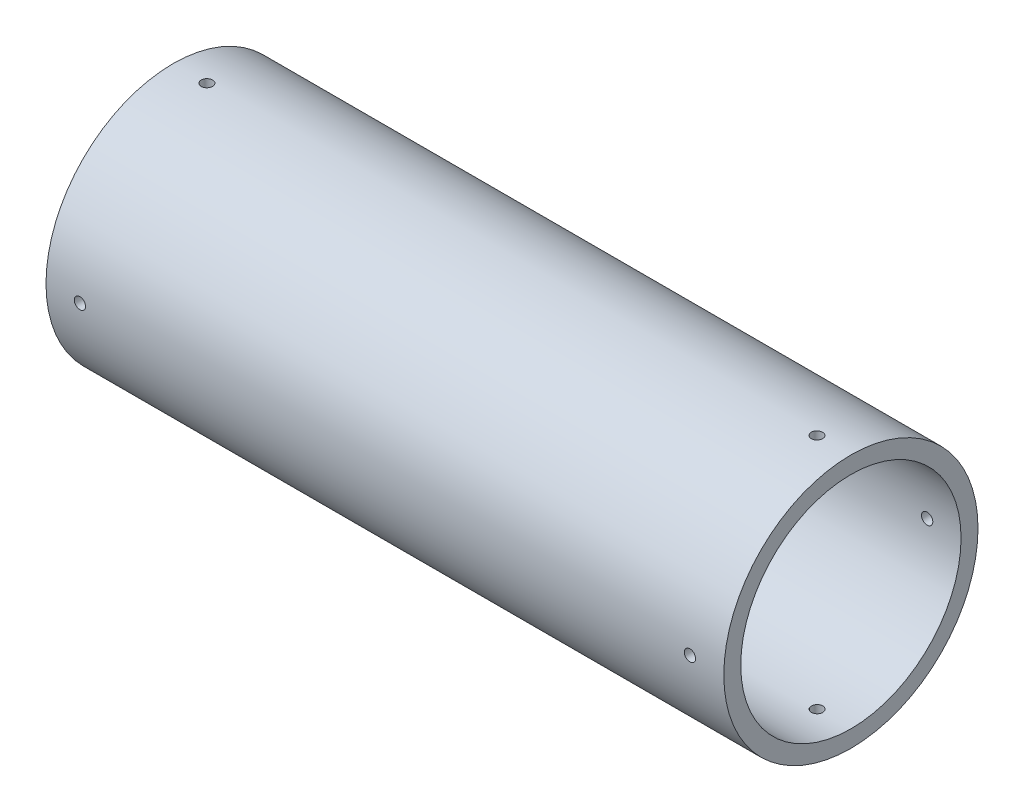
SolidWorks part; units mm, degrees
material "ABS"
ref_plane "Спереди" through (0, 0, 0) normal (0, 0, 1) x (1, 0, 0)
ref_plane "Сверху" through (0, 0, 0) normal (0, 1, 0) x (1, 0, 0)
ref_plane "Справа" through (0, 0, 0) normal (1, 0, 0) x (0, 0, -1)
sketch "Эскиз1" plane through (0, 0, 0) normal (1, 0, 0) x (0, 0, -1)
  circle A0 centre (0, 0) radius 22.5
  circle A1 centre (0, 0) radius 19.5
  dimension "D1" = 45
  dimension "D2" = 39
extrude "Бобышка-Вытянуть1" add sketch "Эскиз1" along normal blind 120
sketch "Эскиз2" plane through (120, 0, 0) normal (1, 0, 0) x (0, 0, -1)
  line L0 (0, 22.5) -> (0, -22.5) construction
  circle A0 centre (0, 0) radius 22.5 construction
ref_plane "Плоскость1" through (0, 22.5, 0) normal (0, 1, 0) x (1, 0, 0)
sketch "Эскиз3" plane through (0, 22.5, 0) normal (0, 1, 0) x (1, 0, 0)
  line L0 (60, 22.5) -> (60, -22.5) construction
  line L1 (120, 22.5) -> (0, 22.5) construction
  line L2 (0, -22.5) -> (120, -22.5) construction
  line L3 (0, 0) -> (120, 0) construction
  line L4 (120, -22.5) -> (120, 22.5) construction
  circle A0 centre (6, 0) radius 1
  circle A1 centre (114, 0) radius 1
  dimension "D1" = 2
  dimension "D3" = 2
  dimension "D2" = 6
  dimension "D4" = 6
extrude "Вырез-Вытянуть1" cut sketch "Эскиз3" against normal blind 10
pattern_circular "Круговой массив1" count 4 over 360 about axis through (120, 0, 0) along (-1, 0, 0) of "Вырез-Вытянуть1"
